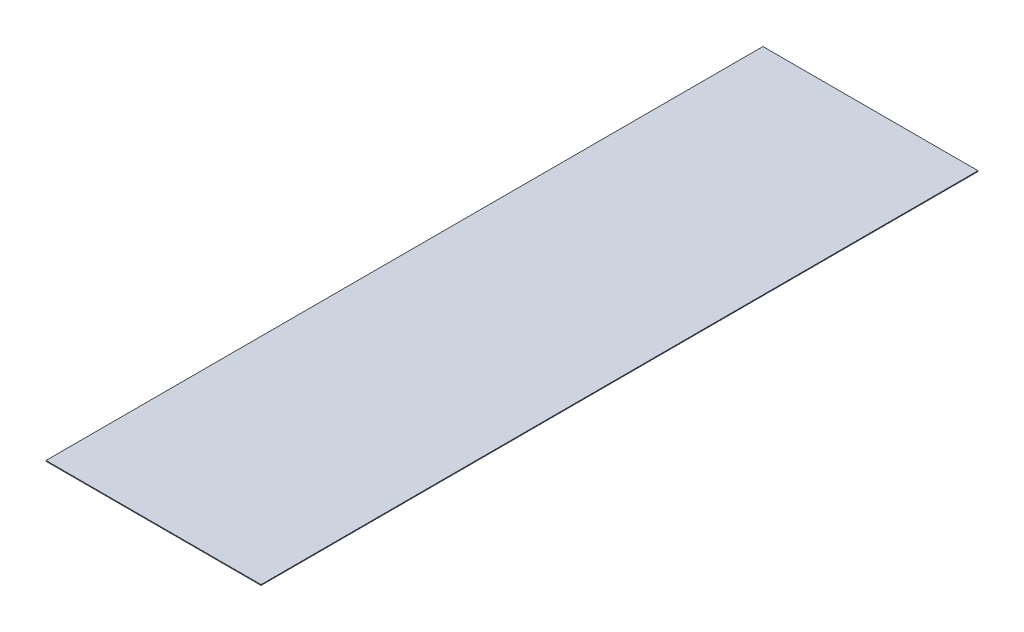
SolidWorks part; units mm, degrees
material "ASTM A36 Acero"
ref_plane "Alzado" through (0, 0, 0) normal (0, 0, 1) x (1, 0, 0)
ref_plane "Planta" through (0, 0, 0) normal (0, 1, 0) x (1, 0, 0)
ref_plane "Vista lateral" through (0, 0, 0) normal (1, 0, 0) x (0, 0, -1)
sketch "Croquis1" plane through (0, 0, 0) normal (0, 1, 0) x (1, 0, 0)
  line L1 (-457.2, -1524) -> (457.2, -1524)
  line L2 (-457.2, -1524) -> (-457.2, 1524)
  line L3 (-457.2, 1524) -> (457.2, 1524)
  line L4 (457.2, -1524) -> (457.2, 1524)
  line L5 (-457.2, -1524) -> (457.2, 1524) construction
  line L6 (-457.2, 1524) -> (457.2, -1524) construction
  point P0 (0, 0)
  dimension "D1" = 3048
  dimension "D2" = 914.4
extrude "Saliente-Extruir1" add sketch "Croquis1" along normal blind 3.2
